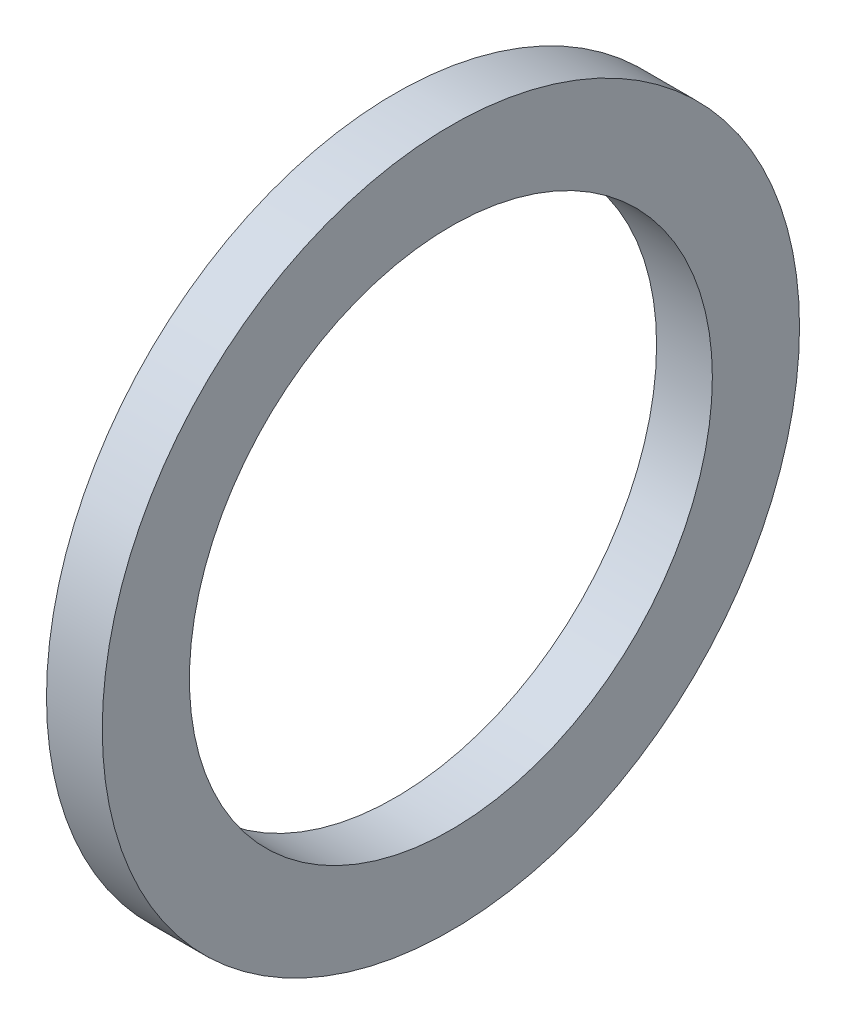
SolidWorks part; units mm, degrees
material "POM Acetal Copolymer"
ref_plane "Front Plane" through (0, 0, 0) normal (0, 0, 1) x (1, 0, 0)
ref_plane "Top Plane" through (0, 0, 0) normal (0, 1, 0) x (1, 0, 0)
ref_plane "Right Plane" through (0, 0, 0) normal (1, 0, 0) x (0, 0, -1)
sketch "Sketch1" plane through (0, 0, 0) normal (1, 0, 0) x (0, 0, -1)
  circle A0 centre (0, 0) radius 2.3813
  circle A1 centre (0, 0) radius 3.175
  dimension "D1" = 4.7625
  dimension "D2" = 6.35
extrude "Boss-Extrude1" add sketch "Sketch1" along normal blind 0.508
